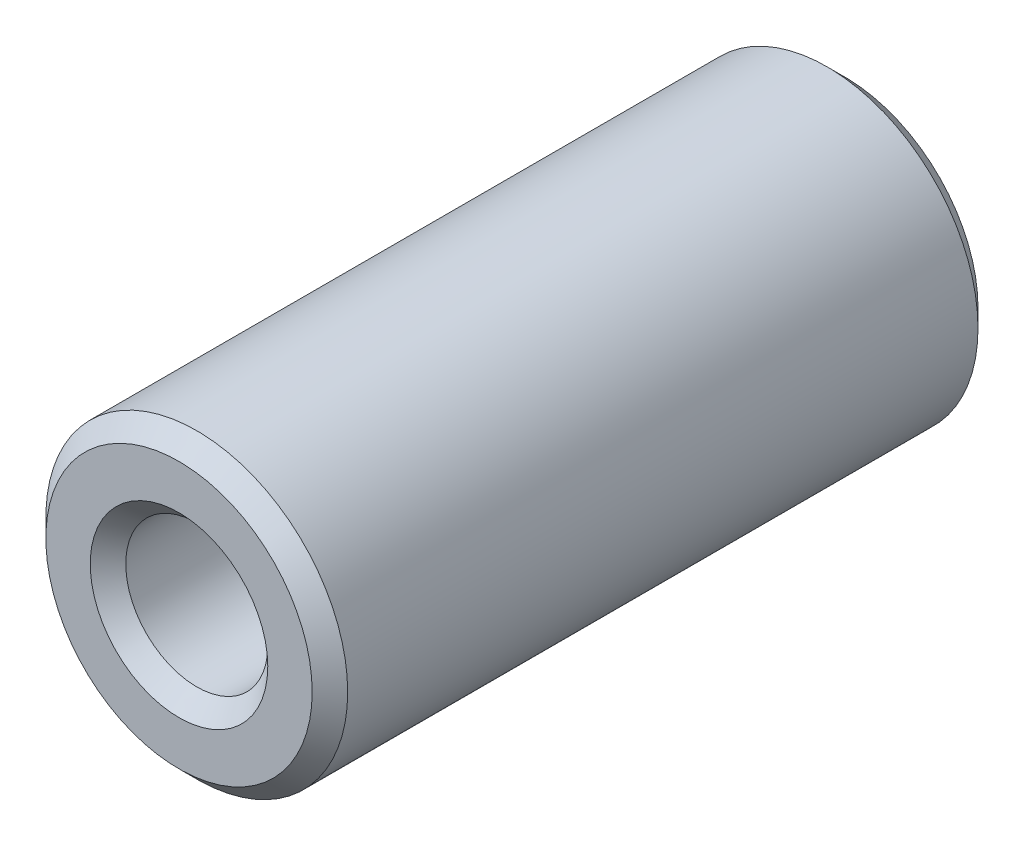
SolidWorks part; units mm, degrees
material "1.7045 (42Cr4)"
ref_plane "Спереди" through (0, 0, 0) normal (0, 0, 1) x (1, 0, 0)
ref_plane "Сверху" through (0, 0, 0) normal (0, 1, 0) x (1, 0, 0)
ref_plane "Справа" through (0, 0, 0) normal (1, 0, 0) x (0, 0, -1)
sketch "Эскиз1" plane through (0, 0, 0) normal (0, 0, 1) x (1, 0, 0)
  circle A0 centre (0, 0) radius 17
  circle A1 centre (0, 0) radius 8
extrude "Бобышка-Вытянуть1" add sketch "Эскиз1" along normal blind 75
chamfer "Фаска1" distance 2 angle 45 4 edges at (8, 0, 0) (8, 0, 75) (17, 0, 75) (17, 0, 0)
